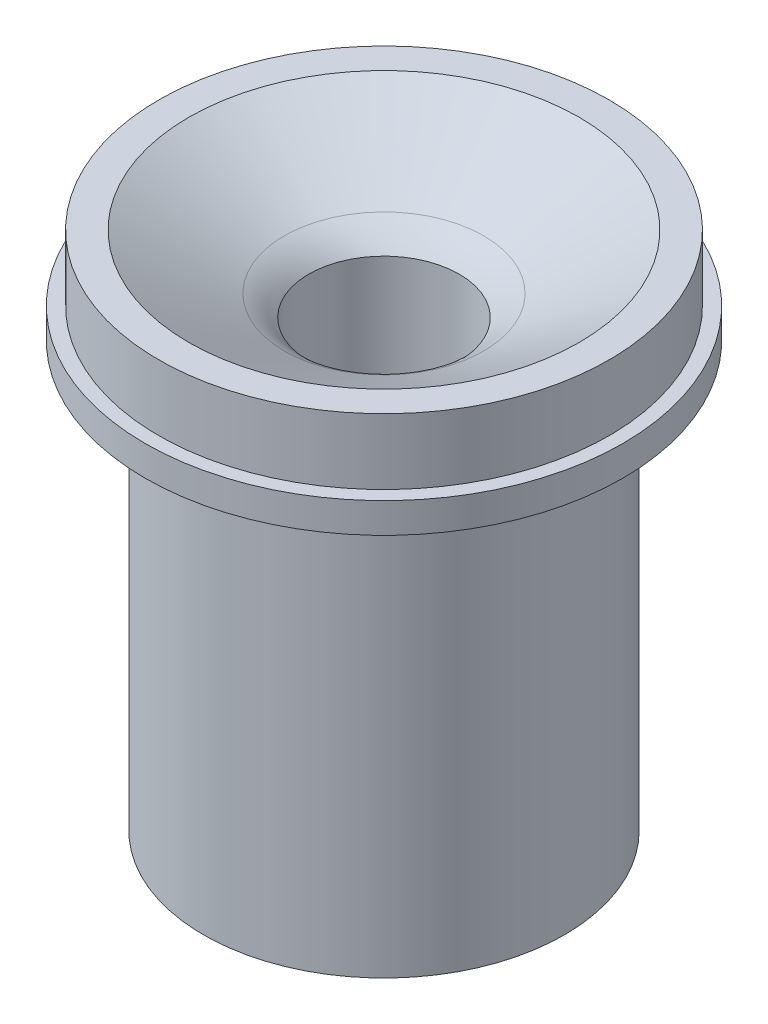
SolidWorks part; units mm, degrees
ref_plane "Front Plane" through (0, 0, 0) normal (0, 0, 1) x (1, 0, 0)
ref_plane "Top Plane" through (0, 0, 0) normal (0, 1, 0) x (1, 0, 0)
ref_plane "Right Plane" through (0, 0, 0) normal (1, 0, 0) x (0, 0, -1)
sketch "Sketch1" plane through (0, 0, 0) normal (0, 0, 1) x (1, 0, 0)
  line L0 (0, 0) -> (0, 60.0489) construction
  line L1 (15.875, -54.9402) -> (5.7719, -17.2349)
  line L2 (5.7719, -17.2349) -> (5.7719, -14.0599)
  line L3 (10.5344, -5.811) -> (20.5994, 0)
  line L4 (20.5994, 0) -> (23.7744, 0)
  line L5 (23.7744, 0) -> (23.7744, -6.9342)
  line L6 (23.7744, -6.9342) -> (25.2095, -6.9342)
  line L7 (25.2095, -6.9342) -> (25.2095, -10.1092)
  line L8 (25.2095, -10.1092) -> (22.2123, -10.1092)
  line L9 (22.2123, -10.1092) -> (22.2123, -11.8872)
  line L10 (22.2123, -11.8872) -> (19.05, -11.8872)
  line L11 (19.05, -11.8872) -> (19.05, -54.9402)
  line L12 (15.875, -54.9402) -> (19.05, -54.9402)
  line L13 (-15.875, -54.9402) -> (-19.05, -54.9402)
  line L14 (-19.05, -11.8872) -> (-19.05, -54.9402)
  line L15 (-22.2123, -11.8872) -> (-19.05, -11.8872)
  line L16 (-22.2123, -10.1092) -> (-22.2123, -11.8872)
  line L17 (-25.2095, -10.1092) -> (-22.2123, -10.1092)
  line L18 (-25.2095, -6.9342) -> (-25.2095, -10.1092)
  line L19 (-23.7744, -6.9342) -> (-25.2095, -6.9342)
  line L20 (-23.7744, 0) -> (-23.7744, -6.9342)
  line L21 (-20.5994, 0) -> (-23.7744, 0)
  line L22 (-10.5344, -5.811) -> (-20.5994, 0)
  line L23 (-5.7719, -17.2349) -> (-5.7719, -14.0599)
  line L24 (-15.875, -54.9402) -> (-5.7719, -17.2349)
  line L25 (-20.447, -11.8872) -> (-19.05, -13.2842)
  line L26 (20.447, -11.8872) -> (19.05, -13.2842)
  arc A0 (5.7719, -14.0599) -> (10.5344, -5.811) centre (15.2969, -14.0599) cw
  arc A1 (-10.5344, -5.811) -> (-5.7719, -14.0599) centre (-15.2969, -14.0599) cw
  point P34 (5.7719, -8.5607)
  point P37 (-5.7719, -8.5607)
  dimension "D15" = 9.525
  dimension "D1" = 50.419
  dimension "D2" = 47.5488
  dimension "D3" = 41.1988
  dimension "D4" = 6.9342
  dimension "D5" = 10.1092
  dimension "D6" = 11.8872
  dimension "D7" = 13.2842
  dimension "D8" = 40.894
  dimension "D9" = 120
  dimension "D10" = 30
  dimension "D11" = 31.75
  dimension "D12" = 38.1
  dimension "D13" = 44.4246
  dimension "D14" = 54.9402
  dimension "D16" = 3.175
revolve "Revolve1" add sketch "Sketch1" angle 360 about L0
sketch "Sketch2" plane through (0, 0, 0) normal (0, 1, 0) x (1, 0, 0)
  circle A0 centre (0, 0) radius 7.9375
  dimension "D1" = 15.875
extrude "Cut-Extrude1" cut sketch "Sketch2" against normal through all both and the other way through all
